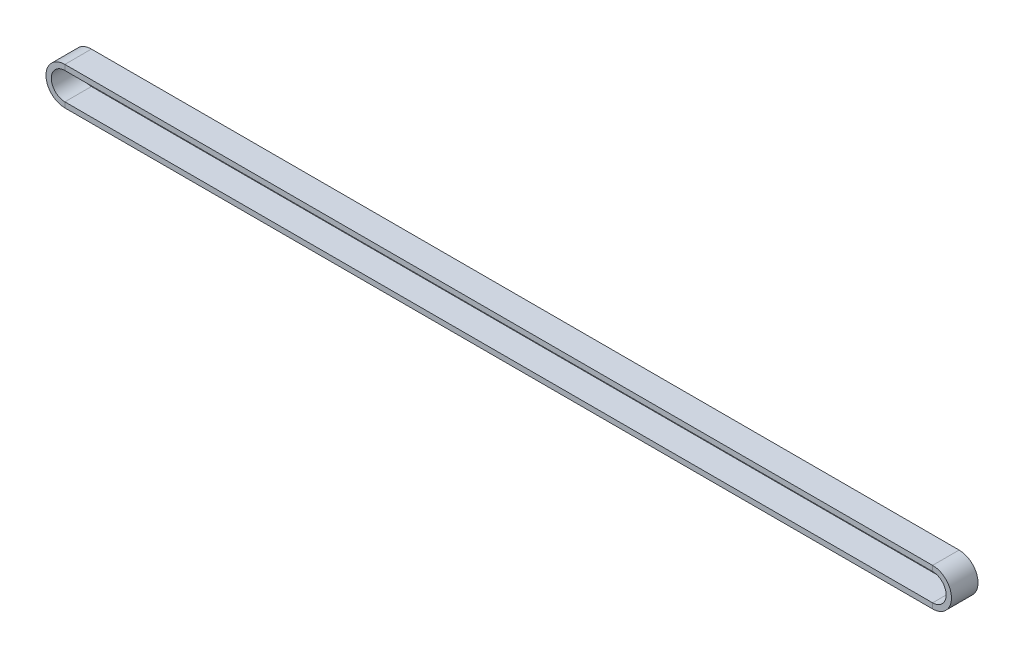
SolidWorks part; units mm, degrees
ref_plane "Front Plane" through (0, 0, 0) normal (0, 0, 1) x (1, 0, 0)
ref_plane "Top Plane" through (0, 0, 0) normal (0, 1, 0) x (1, 0, 0)
ref_plane "Right Plane" through (0, 0, 0) normal (1, 0, 0) x (0, 0, -1)
sketch "Sketch2" plane through (0, 0, 0) normal (0, 0, 1) x (1, 0, 0)
  line L0 (0, 0) -> (1, 0) construction
  line L1 (0, 0) -> (0, 1) construction
  line L2 (0, 18.8878) -> (-327, 18.8878)
  line L3 (-327, 31.1122) -> (0, 31.1122)
  arc A0 (0, 31.1122) -> (0, 18.8878) centre (0, 25) cw
  arc A1 (-327, 18.8878) -> (-327, 31.1122) centre (-327, 25) cw
sketch "Sketch3" plane through (0, 0, 0) normal (1, 0, 0) x (0, 0, -1)
  line L5 (0, 31.1122) -> (0, 18.8878) construction
  line L6 (0, 31.1122) -> (0, 18.8878)
  line L8 (5, 30.1122) -> (-5, 30.1122)
  line L9 (5, 30.1122) -> (5, 32.1122)
  line L10 (5, 32.1122) -> (-5, 32.1122)
  line L11 (-5, 30.1122) -> (-5, 32.1122)
  line L12 (5, 30.1122) -> (-5, 32.1122) construction
  line L13 (5, 32.1122) -> (-5, 30.1122) construction
  dimension "D1" = 10
  dimension "D2" = 2
sweep "Sweep1" add profiles "Sketch3" path "Sketch2"
